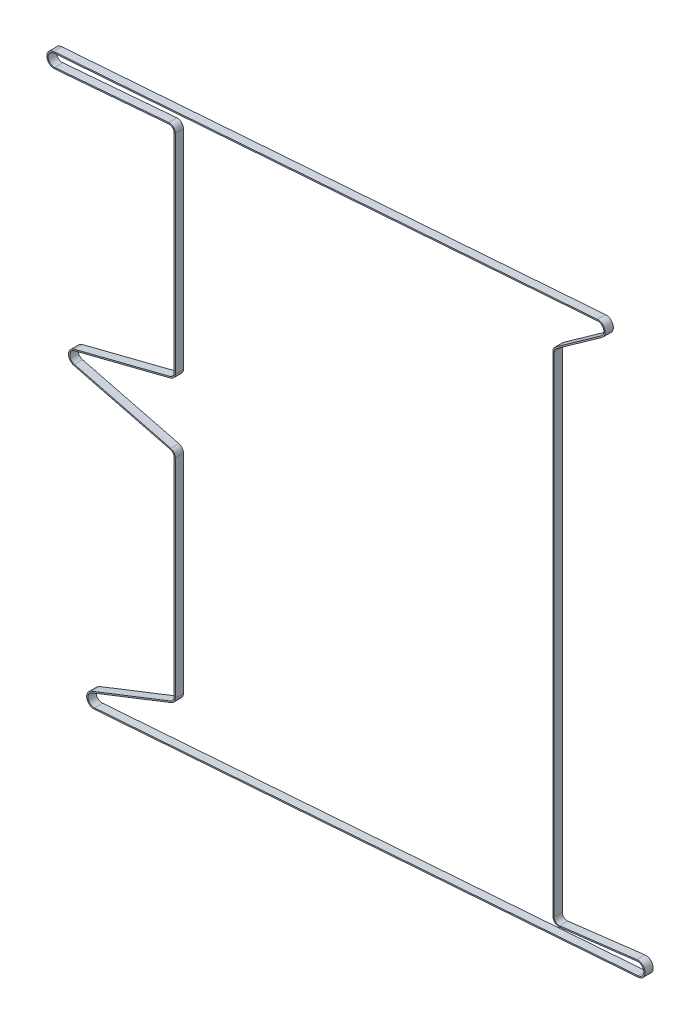
SolidWorks part; units mm, degrees
material "Полиуретан (11671)"
ref_plane "Спереди" through (0, 0, 0) normal (0, 0, 1) x (1, 0, 0)
ref_plane "Сверху" through (0, 0, 0) normal (0, 1, 0) x (1, 0, 0)
ref_plane "Справа" through (0, 0, 0) normal (1, 0, 0) x (0, 0, -1)
sketch "Эскиз2" plane through (0, 0, 0) normal (0, 0, 1) x (1, 0, 0)
  line L0 (0, 0) -> (1, 0) construction
  line L1 (0, 0) -> (0, 1) construction
  line L2 (1.6501, -6.4936) -> (-104.6501, -33.5064)
  line L3 (-104.6501, -46.4936) -> (1.6501, -73.5064)
  line L4 (6.7, -80) -> (6.7, -310)
  line L5 (2.4496, -316.2361) -> (-85.4496, -350.7639)
  line L6 (-82.51, -363.6821) -> (517.49, -319.6821)
  line L7 (516.1972, -306.3483) -> (430.8232, -316.6517)
  line L8 (423.3204, -310) -> (423.3204, 230)
  line L9 (426.138, 235.4605) -> (476.8824, 271.5395)
  line L10 (472.51, 283.6821) -> (-127.49, 239.6821)
  line L11 (-126.4508, 226.3225) -> (-0.5492, 236.6775)
  line L12 (6.7, 230) -> (6.7, 0)
  arc A0 (6.7, 0) -> (1.6501, -6.4936) centre (0, 0) cw
  arc A1 (-104.6501, -33.5064) -> (-104.6501, -46.4936) centre (-103, -40) ccw
  arc A2 (1.6501, -73.5064) -> (6.7, -80) centre (0, -80) cw
  arc A3 (6.7, -310) -> (2.4496, -316.2361) centre (0, -310) cw
  arc A4 (-85.4496, -350.7639) -> (-82.51, -363.6821) centre (-83, -357) ccw
  arc A5 (517.49, -319.6821) -> (516.1972, -306.3483) centre (517, -313) ccw
  arc A6 (430.8232, -316.6517) -> (423.3204, -310) centre (430.0204, -310) cw
  arc A7 (423.3204, 230) -> (426.138, 235.4605) centre (430.0204, 230) cw
  arc A8 (476.8824, 271.5395) -> (472.51, 283.6821) centre (473, 277) ccw
  arc A9 (-127.49, 239.6821) -> (-126.4508, 226.3225) centre (-127, 233) ccw
  arc A10 (-0.5492, 236.6775) -> (6.7, 230) centre (0, 230) cw
extrude "Вытянуть-Тонкостенный1" add sketch "Эскиз2" along normal mid plane 9 thin
